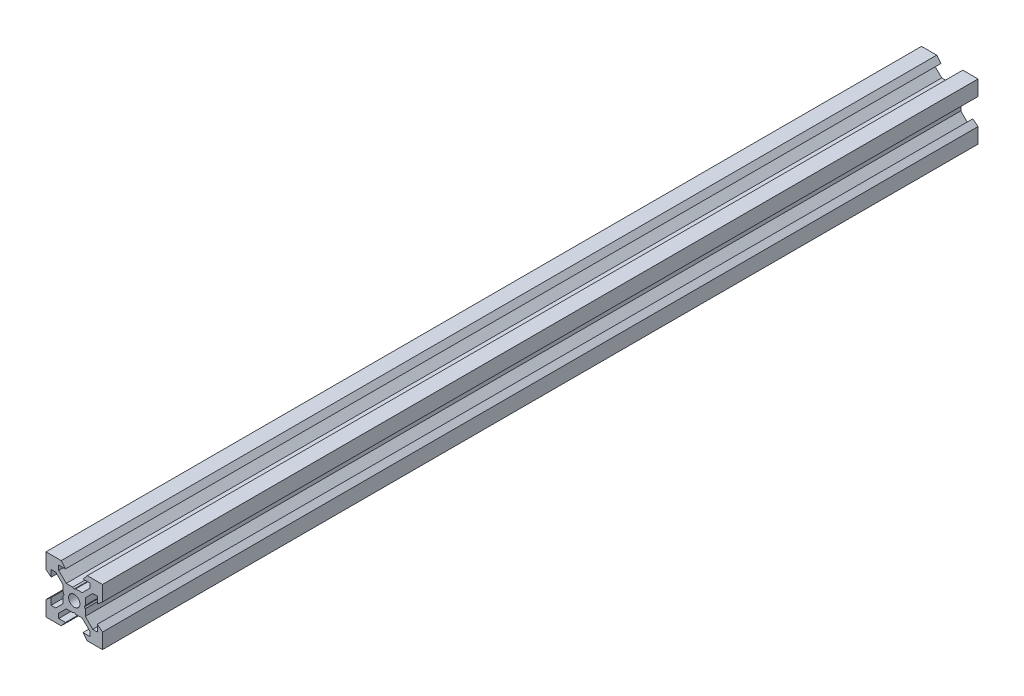
SolidWorks part; units mm, degrees
material "6063-O"
ref_plane "Front Plane" through (0, 0, 0) normal (0, 0, 1) x (1, 0, 0)
ref_plane "Top Plane" through (0, 0, 0) normal (0, 1, 0) x (1, 0, 0)
ref_plane "Right Plane" through (0, 0, 0) normal (1, 0, 0) x (0, 0, -1)
sketch "Sketch1" plane through (0, 0, 0) normal (0, 0, 1) x (1, 0, 0)
  line L0 (10, 10) -> (4.6104, 10) construction
  line L1 (10, 10) -> (10, 4.6104) construction
  line L2 (10, -10) -> (10, -4.6104) construction
  line L3 (10, -10) -> (4.6104, -10) construction
  line L4 (10, 10) -> (10, 4.6104)
  line L5 (6.5607, 5.5) -> (8.2, 5.5)
  line L6 (5.5, 8.2) -> (5.5, 6.5607)
  line L7 (10, 10) -> (4.6104, 10)
  line L8 (10, 10) -> (10, 4.6104)
  line L9 (6.5607, 5.5) -> (3.9, 2.8393)
  line L10 (5.5, 6.5607) -> (2.8393, 3.9)
  line L11 (10, 4.6104) -> (8.2, 3.1)
  line L12 (4.6104, 10) -> (3.1, 8.2)
  line L13 (8.2, 3.1) -> (8.2, 5.5)
  line L14 (3.1, 8.2) -> (5.5, 8.2)
  line L15 (-6.5607, 5.5) -> (-8.2, 5.5)
  line L16 (6.5607, -5.5) -> (8.2, -5.5)
  line L17 (3.1, -8.2) -> (5.5, -8.2)
  line L18 (8.2, -3.1) -> (8.2, -5.5)
  line L19 (4.6104, -10) -> (3.1, -8.2)
  line L20 (10, -4.6104) -> (8.2, -3.1)
  line L21 (0.5196, -3.9) -> (0, -3.6)
  line L22 (0.5196, 3.9) -> (0, 3.6)
  line L23 (3.6, 0) -> (3.9, -0.5196)
  line L24 (3.9, 0.5196) -> (3.6, 0)
  line L25 (3.9, 0.5196) -> (3.9, 2.8393)
  line L26 (2.8393, 3.9) -> (0.5196, 3.9)
  line L27 (3.9, -2.8393) -> (3.9, -0.5196)
  line L28 (2.8393, -3.9) -> (0.5196, -3.9)
  line L29 (5.5, -6.5607) -> (2.8393, -3.9)
  line L30 (6.5607, -5.5) -> (3.9, -2.8393)
  line L31 (10, -10) -> (10, -4.6104)
  line L32 (10, -10) -> (4.6104, -10)
  line L33 (5.5, -8.2) -> (5.5, -6.5607)
  line L34 (-6.5607, -5.5) -> (-8.2, -5.5)
  line L35 (10, -10) -> (10, -4.6104)
  line L36 (0, 0) -> (0, 8.2) construction
  line L37 (-10, -10) -> (-4.6104, -10) construction
  line L38 (-10, -10) -> (-10, -4.6104) construction
  line L39 (-10, 10) -> (-10, 4.6104) construction
  line L40 (-10, 10) -> (-4.6104, 10) construction
  line L41 (-10, -10) -> (-10, -4.6104)
  line L43 (-5.5, -8.2) -> (-5.5, -6.5607)
  line L44 (-10, -10) -> (-4.6104, -10)
  line L45 (-10, -10) -> (-10, -4.6104)
  line L46 (-6.5607, -5.5) -> (-3.9, -2.8393)
  line L47 (-5.5, -6.5607) -> (-2.8393, -3.9)
  line L48 (-2.8393, -3.9) -> (-0.5196, -3.9)
  line L49 (-3.9, -2.8393) -> (-3.9, -0.5196)
  line L50 (-2.8393, 3.9) -> (-0.5196, 3.9)
  line L51 (-3.9, 0.5196) -> (-3.9, 2.8393)
  line L52 (-3.9, 0.5196) -> (-3.6, 0)
  line L53 (-3.6, 0) -> (-3.9, -0.5196)
  line L54 (-0.5196, 3.9) -> (0, 3.6)
  line L55 (-0.5196, -3.9) -> (0, -3.6)
  line L56 (-10, -4.6104) -> (-8.2, -3.1)
  line L57 (-4.6104, -10) -> (-3.1, -8.2)
  line L58 (-8.2, -3.1) -> (-8.2, -5.5)
  line L59 (-3.1, -8.2) -> (-5.5, -8.2)
  line L60 (-10, -10) -> (10, -10) construction
  line L61 (-10, -10) -> (-10, 10) construction
  line L62 (-3.1, 8.2) -> (-5.5, 8.2)
  line L63 (-8.2, 3.1) -> (-8.2, 5.5)
  line L64 (-4.6104, 10) -> (-3.1, 8.2)
  line L65 (-10, 4.6104) -> (-8.2, 3.1)
  line L66 (-5.5, 6.5607) -> (-2.8393, 3.9)
  line L67 (-6.5607, 5.5) -> (-3.9, 2.8393)
  line L68 (-10, 10) -> (-10, 4.6104)
  line L69 (-10, 10) -> (-4.6104, 10)
  line L70 (-5.5, 8.2) -> (-5.5, 6.5607)
  line L71 (-10, 10) -> (10, 10) construction
  line L72 (-10, 10) -> (-10, 4.6104)
  line L73 (10, -10) -> (10, 10) construction
  line L74 (-10, -10) -> (10, 10) construction
  line L75 (-10, 10) -> (10, -10) construction
  circle A0 centre (0, 0) radius 2
  dimension "D7" = 4
  dimension "D1" = 20
  dimension "D2" = 5.3896
  dimension "D3" = 4.5
  dimension "D4" = 50
  dimension "D5" = 1.8
  dimension "D6" = 1.5104
  dimension "D8" = 5.5
  dimension "D9" = 120
  dimension "D10" = 0.3
  dimension "D11" = 2.3197
  dimension "D12" = 7.8
  dimension "D13" = 7.8
  dimension "D14" = 1.5
  dimension "D15" = 2.6607
extrude "Boss-Extrude1" add sketch "Sketch1" along normal mid plane 310 contours L70 L62 L64 L69 L68 L65 L63 L15 L67 L51 L52 L53 L49 L46 L34 L58 L56 L41 L44 L57 L59 L43 L47 L48 L55 L21 L28 L29 L33 L17 L19 L32 L31 L20 L18 L16 L30 L27 L23 L24 L25 L9 L5 L13 L11 L4 L7 L12 L14 L6 L10
